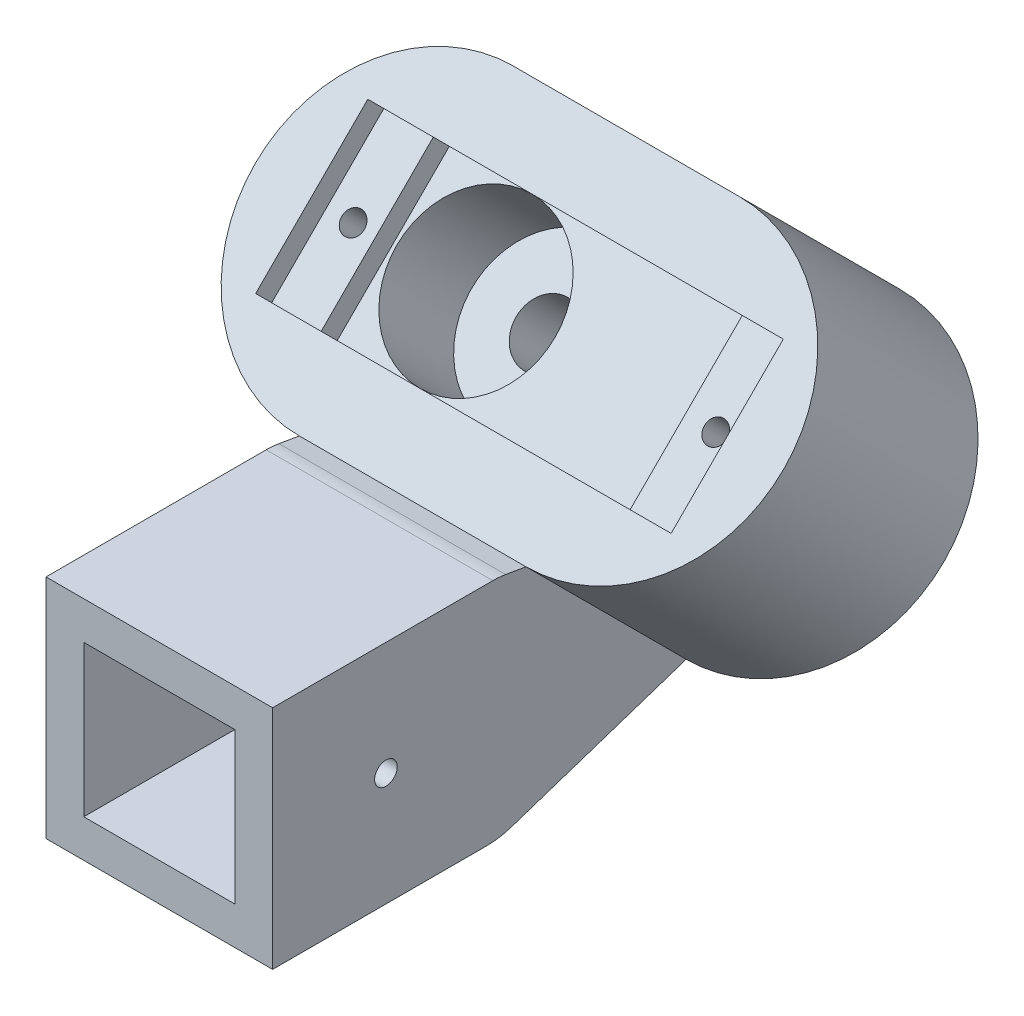
SolidWorks part; units mm, degrees
ref_plane "Front Plane" through (0, 0, 0) normal (0, 0, 1) x (1, 0, 0)
ref_plane "Top Plane" through (0, 0, 0) normal (0, 1, 0) x (1, 0, 0)
ref_plane "Right Plane" through (0, 0, 0) normal (1, 0, 0) x (0, 0, -1)
sketch "Sketch1" plane through (0, 0, 0) normal (0, 0, 1) x (1, 0, 0)
  line L0 (0, 0) -> (0, 2.3333)
  line L1 (-0.0423, 4.2182) -> (3.1811, 4.2182)
  line L2 (3.1811, 4.2182) -> (5.6333, 6.6704)
  line L3 (5.6333, 6.6704) -> (5.6333, 8.2844)
  line L4 (5.6333, 8.2844) -> (2.7333, 8.2844)
  line L5 (2.7333, 8.2844) -> (2.7333, 10)
  line L6 (2.7333, 10) -> (10, 10)
  line L7 (10, 10) -> (10, 2.7333)
  line L8 (10, 2.7333) -> (8.8039, 2.7333)
  line L9 (8.8039, 2.7333) -> (8.8039, 5.6333)
  line L10 (8.8039, 5.6333) -> (6.6704, 5.6333)
  line L11 (6.6704, 5.6333) -> (4.2182, 3.1811)
  line L12 (4.2182, 3.1811) -> (4.2182, 0.0423)
  line L13 (2.3333, 0) -> (0, 0)
  line L14 (5.6333, 6.6704) -> (6.6704, 5.6333) construction
  line L15 (10, 10) -> (5.6333, 5.6333) construction
  line L20 (0, 0) -> (2.3333, 0)
  line L21 (4.2182, 0.0423) -> (4.2182, -3.1811)
  line L22 (4.2182, -3.1811) -> (6.6704, -5.6333)
  line L23 (6.6704, -5.6333) -> (8.2844, -5.6333)
  line L24 (8.2844, -5.6333) -> (8.2844, -2.7333)
  line L25 (8.2844, -2.7333) -> (10, -2.7333)
  line L26 (10, -2.7333) -> (10, -10)
  line L27 (10, -10) -> (2.7333, -10)
  line L28 (2.7333, -10) -> (2.7333, -8.8039)
  line L29 (2.7333, -8.8039) -> (5.6333, -8.8039)
  line L30 (5.6333, -8.8039) -> (5.6333, -6.6704)
  line L31 (5.6333, -6.6704) -> (3.1811, -4.2182)
  line L32 (3.1811, -4.2182) -> (0.0423, -4.2182)
  line L33 (0, -2.3333) -> (0, 0)
  line L34 (6.6704, -5.6333) -> (5.6333, -6.6704) construction
  line L35 (10, -10) -> (5.6333, -5.6333) construction
  line L36 (0, 0) -> (0, -2.3333)
  line L37 (0.0423, -4.2182) -> (-3.1811, -4.2182)
  line L38 (-3.1811, -4.2182) -> (-5.6333, -6.6704)
  line L39 (-5.6333, -6.6704) -> (-5.6333, -8.2844)
  line L40 (-5.6333, -8.2844) -> (-2.7333, -8.2844)
  line L41 (-2.7333, -8.2844) -> (-2.7333, -10)
  line L42 (-2.7333, -10) -> (-10, -10)
  line L43 (-10, -10) -> (-10, -2.7333)
  line L44 (-10, -2.7333) -> (-8.8039, -2.7333)
  line L45 (-8.8039, -2.7333) -> (-8.8039, -5.6333)
  line L46 (-8.8039, -5.6333) -> (-6.6704, -5.6333)
  line L47 (-6.6704, -5.6333) -> (-4.2182, -3.1811)
  line L48 (-4.2182, -3.1811) -> (-4.2182, -0.0423)
  line L49 (-2.3333, 0) -> (0, 0)
  line L50 (-5.6333, -6.6704) -> (-6.6704, -5.6333) construction
  line L51 (-10, -10) -> (-5.6333, -5.6333) construction
  line L52 (0, 0) -> (-2.3333, 0)
  line L53 (-4.2182, -0.0423) -> (-4.2182, 3.1811)
  line L54 (-4.2182, 3.1811) -> (-6.6704, 5.6333)
  line L55 (-6.6704, 5.6333) -> (-8.2844, 5.6333)
  line L56 (-8.2844, 5.6333) -> (-8.2844, 2.7333)
  line L57 (-8.2844, 2.7333) -> (-10, 2.7333)
  line L58 (-10, 2.7333) -> (-10, 10)
  line L59 (-10, 10) -> (-2.7333, 10)
  line L60 (-2.7333, 10) -> (-2.7333, 8.8039)
  line L61 (-2.7333, 8.8039) -> (-5.6333, 8.8039)
  line L62 (-5.6333, 8.8039) -> (-5.6333, 6.6704)
  line L63 (-5.6333, 6.6704) -> (-3.1811, 4.2182)
  line L64 (-3.1811, 4.2182) -> (-0.0423, 4.2182)
  line L65 (0, 2.3333) -> (0, 0)
  line L66 (-6.6704, 5.6333) -> (-5.6333, 6.6704) construction
  line L67 (-10, 10) -> (-5.6333, 5.6333) construction
  line L69 (-15, 15) -> (15, 15)
  line L70 (-15, 15) -> (-15, -15)
  line L71 (-15, -15) -> (15, -15)
  line L72 (15, 15) -> (15, -15)
  line L73 (-15, 15) -> (15, -15) construction
  line L74 (-15, -15) -> (15, 15) construction
  arc A0 (0, 2.3333) -> (2.3333, 0) centre (0, 0) cw
  circle A1 centre (7.8167, 7.8167) radius 1.4
  arc A2 (2.3333, 0) -> (0, -2.3333) centre (0, 0) cw
  circle A3 centre (7.8167, -7.8167) radius 1.4
  arc A4 (0, -2.3333) -> (-2.3333, 0) centre (0, 0) cw
  circle A5 centre (-7.8167, -7.8167) radius 1.4
  arc A6 (-2.3333, 0) -> (0, 2.3333) centre (0, 0) cw
  circle A7 centre (-7.8167, 7.8167) radius 1.4
  dimension "D10" = 2.3333
  dimension "D11" = 2.8
  dimension "D1" = 10
  dimension "D2" = 10
  dimension "D3" = 2.7333
  dimension "D4" = 5.6333
  dimension "D5" = 2.7333
  dimension "D6" = 5.6333
  dimension "D7" = 1.4667
  dimension "D8" = 135
  dimension "D9" = 135
  dimension "D13" = 30
  dimension "D14" = 30
  dimension "D12" = 4
extrude "Boss-Extrude1" add sketch "Sketch1" along normal blind 30 contours L64 L63 L62 L61 L60 L59 L58 L57 L56 L55 L54 L53 L48 L47 L46 L45 L44 L43 L42 L41 L40 L39 L38 L37 L32 L31 L30 L29 L28 L27 L26 L25 L24 L23 L22 L21 L12 L11 L10 L9 L8 L7 L6 L5 L4 L3 L2 L1 A7 | L70 L71 L72 L69
sketch "Sketch2" plane through (15, 0, 0) normal (1, 0, 0) x (0, 0, -1)
  line L0 (0, 15) -> (0, 25) construction
  line L1 (7.0711, 17.9289) -> (22.2111, 33.069) construction
  line L2 (0, 15) -> (42.0182, 15) construction
  line L3 (7.0711, 17.9289) -> (-2.0985, 27.0985) construction
  arc A0 (0, 15) -> (7.0711, 17.9289) centre (0, 25) ccw construction
  dimension "D1" = 10
  dimension "D2" = 45
  dimension "D3" = 90
ref_plane "Plane3" through (15, 17.9289, -7.0711) normal (0, 0.7071, 0.7071) x (1, 0, 0)
sketch "Sketch9" plane through (15, 17.9289, -7.0711) normal (0, 0.7071, 0.7071) x (1, 0, 0)
  line L0 (0, 15) -> (-30, 15) construction
  line L1 (0, -5) -> (-30, -5)
  line L2 (0, 35) -> (-30, 35)
  arc A0 (0, -5) -> (0, 35) centre (0, 15) ccw
  arc A1 (-30, 35) -> (-30, -5) centre (-30, 15) ccw
  point P2 (-15, 15)
  dimension "D2" = 20
  dimension "D1" = 30
  dimension "D3" = 15
extrude "Boss-Extrude3" add sketch "Sketch9" against normal blind 30 separate body
sketch "Sketch16" plane through (0, 8.9645, -8.9645) normal (0, -0.7071, 0.7071) x (1, 0, 0)
  line L1 (-15, 7.6777) -> (15, 7.6777)
  line L2 (-15, 7.6777) -> (-15, -22.3223)
  line L3 (-15, -22.3223) -> (15, -22.3223)
  line L4 (15, 7.6777) -> (15, -22.3223)
sketch "Sketch17" plane through (0, 0, 0) normal (0, 0, -1) x (-1, 0, 0)
  line L1 (15, 15) -> (-15, 15)
  line L2 (15, 15) -> (15, -15)
  line L3 (15, -15) -> (-15, -15)
  line L4 (-15, 15) -> (-15, -15)
loft "Loft5" add profiles "Sketch16", "Sketch17"
sketch "Sketch19" plane through (0, 5.4289, 5.4289) normal (0, 0.7071, 0.7071) x (1, 0, 0)
  line L0 (0, 12.6777) -> (0, 52.6777) construction
  line L1 (15, 12.6777) -> (-15, 12.6777) construction
  line L2 (15, 52.6777) -> (-15, 52.6777) construction
  line L4 (27.5, 22.1777) -> (-27.5, 22.1777)
  line L5 (27.5, 22.1777) -> (27.5, 43.1777)
  line L6 (27.5, 43.1777) -> (-27.5, 43.1777)
  line L7 (-27.5, 22.1777) -> (-27.5, 43.1777)
  line L8 (27.5, 22.1777) -> (-27.5, 43.1777) construction
  line L9 (27.5, 43.1777) -> (-27.5, 22.1777) construction
  point P6 (0, 32.6777)
  dimension "D1" = 21
  dimension "D2" = 55
extrude "Cut-Extrude2" cut sketch "Sketch19" against normal blind 3
sketch "Sketch20" plane through (0, 3.3076, 3.3076) normal (0, 0.7071, 0.7071) x (1, 0, 0)
  line L0 (0, 22.1777) -> (0, 42.7687) construction
  line L1 (-27.5, 22.1777) -> (27.5, 22.1777) construction
  line L2 (27.5, 22.1777) -> (27.5, 43.1777) construction
  circle A0 centre (24, 32.4732) radius 1.5
  circle A2 centre (-24, 32.4732) radius 1.5
  dimension "D2" = 3
  dimension "D3" = 3
  dimension "D1" = 3.5
  dimension "D4" = 48
extrude "Cut-Extrude3" cut sketch "Sketch20" against normal blind 10
sketch "Sketch21" plane through (0, 3.3076, 3.3076) normal (0, 0.7071, 0.7071) x (1, 0, 0)
  line L0 (0, 22.1777) -> (0, 43.1777) construction
  line L5 (-27.5, 22.1777) -> (27.5, 22.1777) construction
  line L6 (27.5, 43.1777) -> (-27.5, 43.1777) construction
  circle A0 centre (-10, 32.6777) radius 10.5
  point P2 (0, 32.6777)
  dimension "D1" = 21
  dimension "D2" = 10
extrude "Cut-Extrude4" cut sketch "Sketch21" against normal blind 30
sketch "Sketch22" plane through (0, 3.3076, 3.3076) normal (0, 0.7071, 0.7071) x (1, 0, 0)
  line L0 (27.5, 22.1777) -> (27.5, 43.1777) construction
  line L1 (19.95, 22.1777) -> (-20.95, 22.1777)
  line L2 (19.95, 22.1777) -> (19.95, 43.1777)
  line L3 (19.95, 43.1777) -> (-20.95, 43.1777)
  line L4 (-20.95, 22.1777) -> (-20.95, 43.1777)
  line L5 (-10, 22.1777) -> (27.5, 22.1777) construction
  dimension "D1" = 7.55
  dimension "D2" = 21
  dimension "D3" = 40.9
extrude "Cut-Extrude7" cut sketch "Sketch22" against normal blind 3
fillet "Fillet2" radius 10 1 edges at (0, 15, 0)
fillet "Fillet3" radius 10 1 edges at (0, -15, 0)
sketch "Sketch18" plane through (0, 5.4289, 5.4289) normal (0, 0.7071, 0.7071) x (1, 0, 0)
  line L0 (0, 12.6777) -> (0, 52.6777) construction
  line L1 (15, 12.6777) -> (-15, 12.6777) construction
  line L2 (15, 52.6777) -> (-15, 52.6777) construction
  line L4 (27.5, 22.1777) -> (-27.5, 22.1777)
  line L5 (27.5, 22.1777) -> (27.5, 43.1777)
  line L6 (27.5, 43.1777) -> (-27.5, 43.1777)
  line L7 (-27.5, 22.1777) -> (-27.5, 43.1777)
  line L8 (27.5, 22.1777) -> (-27.5, 43.1777) construction
  line L9 (27.5, 43.1777) -> (-27.5, 22.1777) construction
  point P6 (0, 32.6777)
  dimension "D1" = 21
  dimension "D2" = 55
sketch "Sketch23" plane through (15, 0, 0) normal (1, 0, 0) x (0, 0, -1)
  line L0 (-30, 15) -> (-30, -15) construction
  circle A0 centre (-15, 0) radius 1.5
  dimension "D1" = 3
  dimension "D2" = 15
extrude "Cut-Extrude8" cut sketch "Sketch23" against normal blind 30
sketch "Sketch24" plane through (0, -15.7843, -15.7843) normal (0, -0.7071, -0.7071) x (1, 0, 0)
  line L1 (1.5469, -43.1866) -> (-22.4469, -43.1866)
  line L2 (1.5469, -43.1866) -> (1.5469, -21.7598)
  line L3 (1.5469, -21.7598) -> (-22.4469, -21.7598)
  line L4 (-22.4469, -43.1866) -> (-22.4469, -21.7598)
  line L5 (1.5469, -43.1866) -> (-22.4469, -21.7598) construction
  line L6 (1.5469, -21.7598) -> (-22.4469, -43.1866) construction
  circle A0 centre (-10.45, -32.4732) radius 4
  dimension "D1" = 8
extrude "Boss-Extrude4" add sketch "Sketch24" against normal blind 10
sketch "Sketch25" plane through (0, 0, 30) normal (0, 0, 1) x (1, 0, 0)
  line L1 (-10, 10) -> (10, 10)
  line L2 (-10, 10) -> (-10, -10)
  line L3 (-10, -10) -> (10, -10)
  line L4 (10, 10) -> (10, -10)
  line L5 (-10, 10) -> (10, -10) construction
  line L6 (-10, -10) -> (10, 10) construction
  point P0 (0, 0)
extrude "Cut-Extrude10" cut sketch "Sketch25" against normal blind 30
